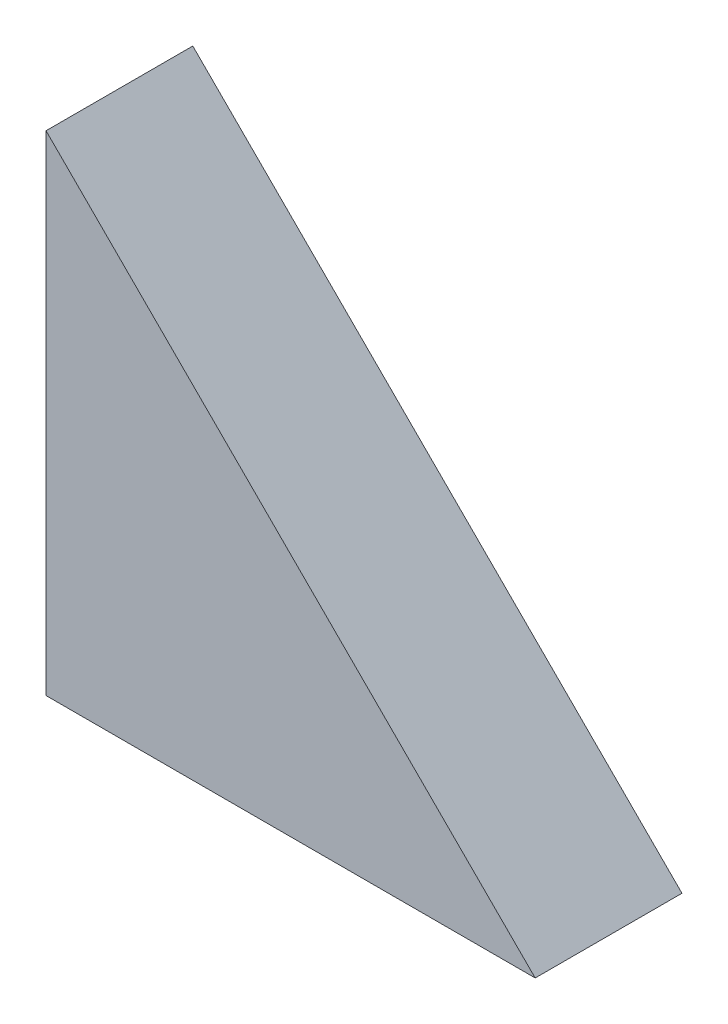
SolidWorks part; units mm, degrees
ref_plane "Front Plane" through (0, 0, 0) normal (0, 0, 1) x (1, 0, 0)
ref_plane "Top Plane" through (0, 0, 0) normal (0, 1, 0) x (1, 0, 0)
ref_plane "Right Plane" through (0, 0, 0) normal (1, 0, 0) x (0, 0, -1)
sketch "Sketch1" plane through (0, 0, 0) normal (0, 0, 1) x (1, 0, 0)
  line L0 (-36.1089, 118.322) -> (-36.1089, 54.822)
  line L1 (-36.1089, 54.822) -> (27.3911, 54.822)
  line L3 (27.3911, 54.822) -> (-36.1089, 118.322)
  dimension "D1" = 63.5
extrude "Boss-Extrude1" add sketch "Sketch1" along normal mid plane 19.05
